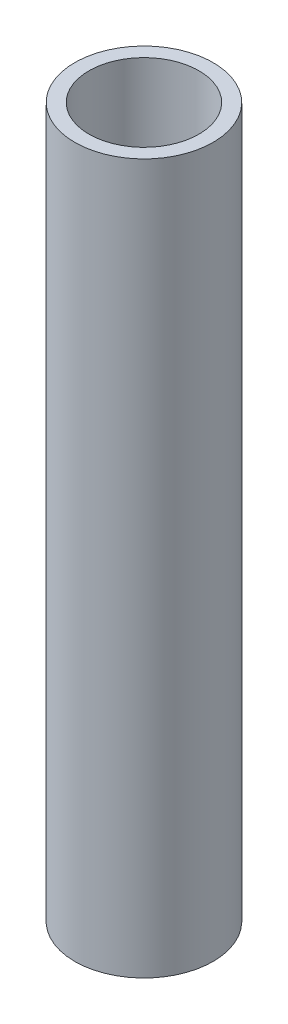
SolidWorks part; units mm, degrees
ref_plane "Front Plane" through (0, 0, 0) normal (0, 0, 1) x (1, 0, 0)
ref_plane "Top Plane" through (0, 0, 0) normal (0, 1, 0) x (1, 0, 0)
ref_plane "Right Plane" through (0, 0, 0) normal (1, 0, 0) x (0, 0, -1)
sketch "草圖1" plane through (0, 0, 0) normal (0, 1, 0) x (1, 0, 0)
  circle A0 centre (0, 0) radius 1.95
  circle A2 centre (0, 0) radius 1.55
  dimension "D1" = 3.9
  dimension "D2" = 3.1
extrude "填料-伸長1" add sketch "草圖1" along normal blind 20
